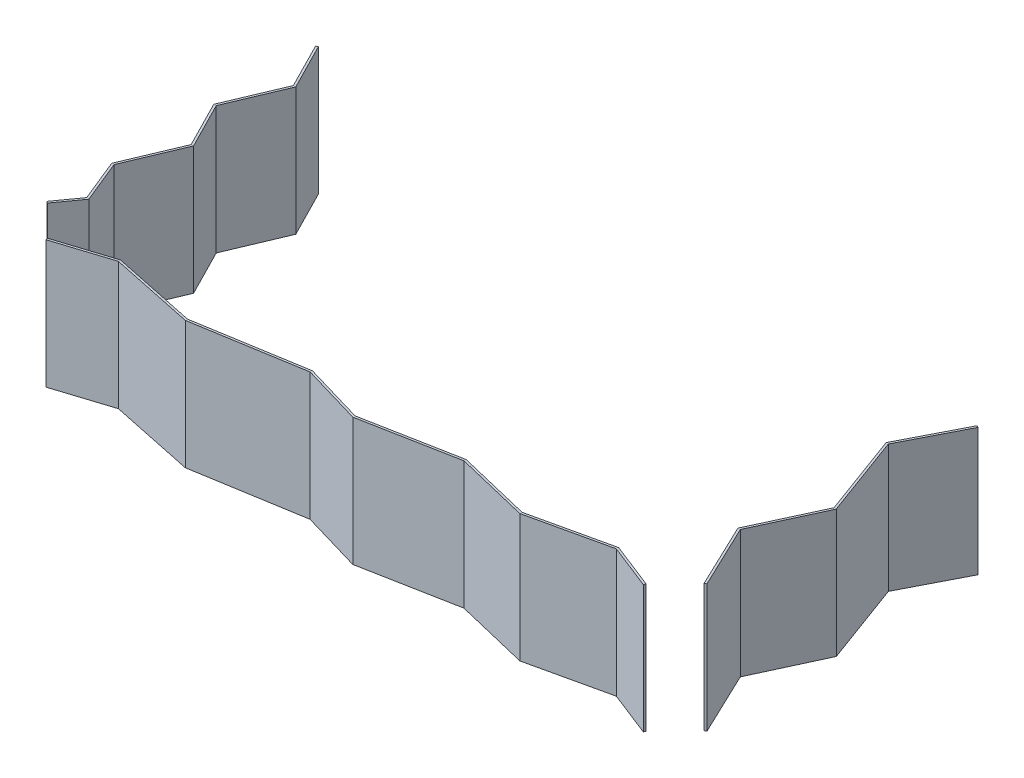
SolidWorks part; units mm, degrees
ref_plane "Front Plane" through (0, 0, 0) normal (0, 0, 1) x (1, 0, 0)
ref_plane "Top Plane" through (0, 0, 0) normal (0, 1, 0) x (1, 0, 0)
ref_plane "Right Plane" through (0, 0, 0) normal (1, 0, 0) x (0, 0, -1)
other "Graphic1"
other "Graphic (Closed) -1"
sketch "Sketch1" plane through (0, 0, 0) normal (0, 1, 0) x (1, 0, 0)
  line L0 (-5.345, 2.9232) -> (-4.7912, 1.837)
  line L1 (-4.7912, 1.837) -> (-5.345, 0.521)
  line L2 (-5.345, 0.521) -> (-4.7912, -0.5652)
  line L3 (-4.7912, -0.5652) -> (-5.345, -1.8812)
  line L4 (-5.345, -1.8812) -> (-4.9376, -2.8806)
  line L5 (-4.9376, -2.8806) -> (-5.345, -3.4468)
  line L6 (-4.63, -4.1618) -> (-3.3275, -3.7458)
  line L7 (-3.3275, -3.7458) -> (-1.3368, -4.1625)
  line L8 (-1.3368, -4.1625) -> (1.1817, -3.7458)
  line L9 (1.1817, -3.7458) -> (2.6024, -4.1625)
  line L10 (2.6024, -4.1625) -> (4.7948, -3.7458)
  line L11 (4.7948, -3.7458) -> (6.5268, -4.1625)
  line L12 (6.5268, -4.1625) -> (8.3798, -3.7458)
  line L13 (8.3798, -3.7458) -> (9.44, -4.1618)
  line L14 (10.155, 2.9232) -> (9.44, 1.5308)
  line L15 (9.44, 1.5308) -> (10.1527, -0.4055)
  line L16 (10.1527, -0.4055) -> (9.44, -1.9484)
  line L17 (9.44, -1.9484) -> (10.155, -3.4468)
extrude "Extrude-Thin10" add sketch "Sketch1" against normal blind 3 from offset 0.4761 thin
